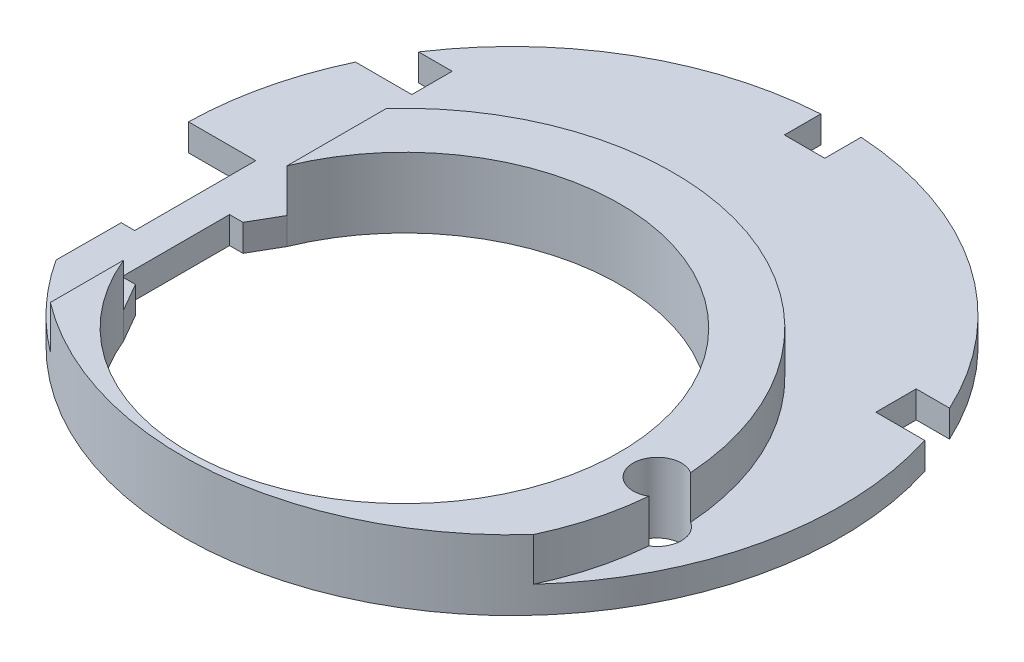
SolidWorks part; units mm, degrees
ref_plane "Front Plane" through (0, 0, 0) normal (0, 0, 1) x (1, 0, 0)
ref_plane "Top Plane" through (0, 0, 0) normal (0, 1, 0) x (1, 0, 0)
ref_plane "Right Plane" through (0, 0, 0) normal (1, 0, 0) x (0, 0, -1)
sketch "Sketch1" plane through (0, 0, 0) normal (0, 1, 0) x (1, 0, 0)
  line L5 (-0.75, 12.227) -> (-0.75, 10.875)
  line L6 (0.75, 12.227) -> (0.75, 10.875)
  line L7 (0.75, 10.875) -> (-0.75, 10.875)
  line L13 (-11.068, 5.25) -> (-8.975, 5.25)
  line L14 (-8.975, 5.25) -> (-8.975, 6.75)
  line L15 (-8.975, 6.75) -> (-10.2225, 6.75)
  line L20 (11.1149, 5.15) -> (9.875, 5.15)
  line L21 (9.875, 5.15) -> (9.875, 3.65)
  line L22 (9.875, 3.65) -> (11.6936, 3.65)
  line L23 (-11.7455, -4.2772) -> (-10.2515, -4.2772)
  line L27 (-10.2515, -4.2772) -> (-10.262, -6.6899)
  arc A0 (-0.75, 12.227) -> (-10.2225, 6.75) centre (0, 0) ccw
  arc A1 (-11.068, 5.25) -> (-11.479, -4.2772) centre (0, 0) ccw
  arc A4 (-10.262, -6.6899) -> (11.6936, 3.65) centre (0, 0) ccw
  arc A5 (11.1149, 5.15) -> (0.75, 12.227) centre (0, 0) ccw
extrude "Boss-Extrude1" add sketch "Sketch1" along normal blind 1 contours L20 A5 L6 L7 L5 A0 L15 L14 L13 A1 L23 L27 A4 L22 L21
sketch "Sketch3" plane through (0, 1, 0) normal (0, 1, 0) x (1, 0, 0)
  line L0 (-7.4007, -0.962) -> (-7.4007, 2.7253)
  line L1 (-7.4007, -7.038) -> (-7.4007, -9.7618)
  circle A0 centre (0, 0) radius 12.25
  circle A1 centre (0, -4) radius 8
  circle A2 centre (0, -4) radius 10
  point P12 (0, 0)
  point P13 (0, 0)
extrude "Boss-Extrude2" add sketch "Sketch3" along normal blind 1.6
sketch "Sketch2" plane through (0, 1, 0) normal (0, 1, 0) x (1, 0, 0)
  line L0 (-9.748, -4.2772) -> (-9.748, 0.2228)
  line L1 (-9.748, 0.2228) -> (-12.248, 0.2228)
  line L2 (-8, -2) -> (-8, -6)
  line L3 (-8, -2) -> (-7.4007, -0.962)
  line L4 (-8, -2) -> (-8.5, -2)
  line L5 (-8, -2) -> (-8, -6)
  line L6 (-8, -6) -> (-8.5, -6)
  line L7 (-8.5, -2) -> (-8.5, -6)
  line L8 (-8, -6) -> (-7.4007, -7.038)
  line L9 (-10.2515, -4.2772) -> (-9.748, -4.2772)
  circle A0 centre (0, -4) radius 8
  arc A1 (-11.068, 5.25) -> (-11.479, -4.2772) centre (0, 0) ccw construction
  circle A2 centre (9.5, -4.1) radius 0.9
  point P12 (-8, -4)
extrude "Cut-Extrude1" cut sketch "Sketch2" against normal through all both and the other way through all
